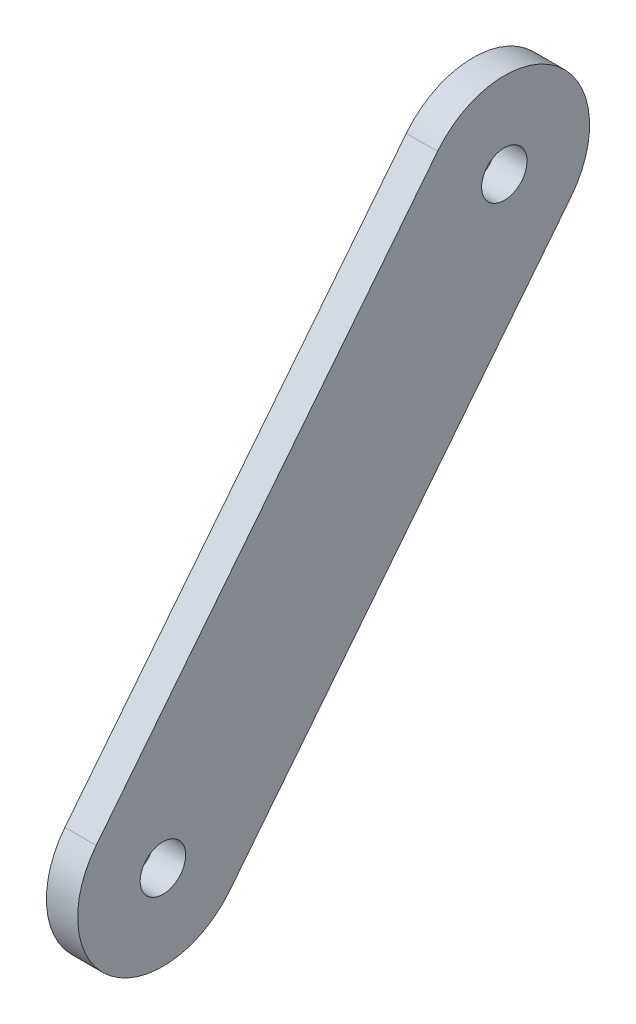
SolidWorks part; units mm, degrees
ref_plane "Спереди" through (0, 0, 0) normal (0, 0, 1) x (1, 0, 0)
ref_plane "Сверху" through (0, 0, 0) normal (0, 1, 0) x (1, 0, 0)
ref_plane "Справа" through (0, 0, 0) normal (1, 0, 0) x (0, 0, -1)
sketch "Эскиз2" plane through (0, 0, 0) normal (1, 0, 0) x (0, 0, -1)
  line L1 (64.8794, 21.3476) -> (124.9581, 97.0695)
  line L3 (41.378, 39.9939) -> (101.4567, 115.7158)
  circle A0 centre (113.2074, 106.3927) radius 4
  arc A1 (41.378, 39.9939) -> (64.8794, 21.3476) centre (53.1287, 30.6707) ccw
  arc A2 (124.9581, 97.0695) -> (101.4567, 115.7158) centre (113.2074, 106.3927) ccw
  circle A3 centre (53.1287, 30.6707) radius 4
extrude "Вытянуть2" add sketch "Эскиз2" along normal blind 5.5
